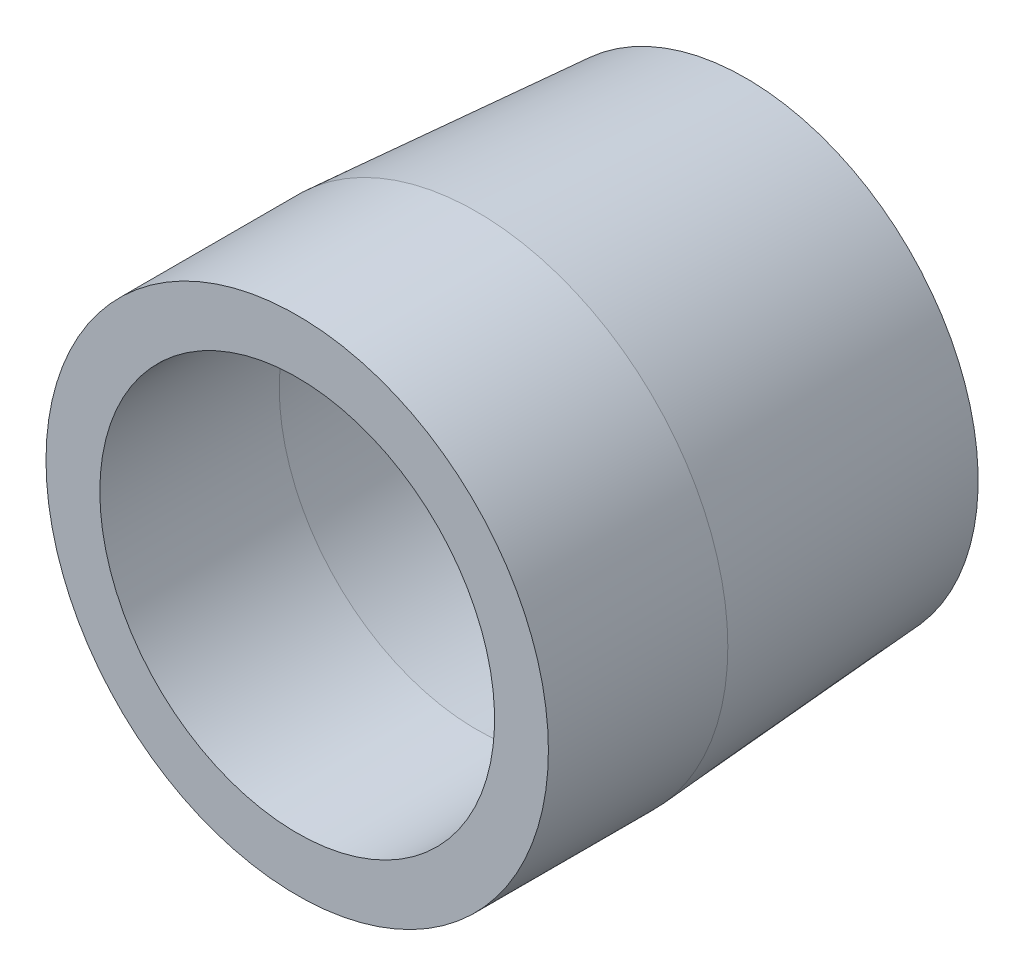
SolidWorks part; units mm, degrees
ref_plane "Plan de face" through (0, 0, 0) normal (0, 0, 1) x (1, 0, 0)
ref_plane "Plan de dessus" through (0, 0, 0) normal (0, 1, 0) x (1, 0, 0)
ref_plane "Plan de droite" through (0, 0, 0) normal (1, 0, 0) x (0, 0, -1)
sketch "Esquisse1" plane through (0, 0, 0) normal (0, 0, 1) x (1, 0, 0)
  circle A0 centre (0, 0) radius 28
extrude "Boss.-Extru.1" add sketch "Esquisse1" along normal blind 20
sketch "Esquisse2" plane through (0, 0, 0) normal (0, 0, -1) x (-1, 0, 0)
  circle A0 centre (0, 0) radius 22
extrude "Enlèv. mat.-Extru.1" cut sketch "Esquisse2" against normal blind 20
sketch "Esquisse3" plane through (0, 0, 0) normal (0, 0, -1) x (-1, 0, 0)
  arc A0 (28, 0) -> (-28, 0) centre (0, 0) cw
  circle A1 centre (0, 0) radius 28 construction
  arc A2 (22, 0) -> (-22, 0) centre (0, 0) cw
  circle A3 centre (0, 0) radius 22 construction
  arc A4 (22, 0) -> (-22, 0) centre (0, 0) ccw
  arc A5 (28, 0) -> (-28, 0) centre (0, 0) ccw
  circle M1 centre (0, 0) radius 22
  circle M2 centre (0, 0) radius 28
extrude "Boss.-Extru.2" add sketch "Esquisse3" along normal blind 30 draft 4 contours M2 M1
